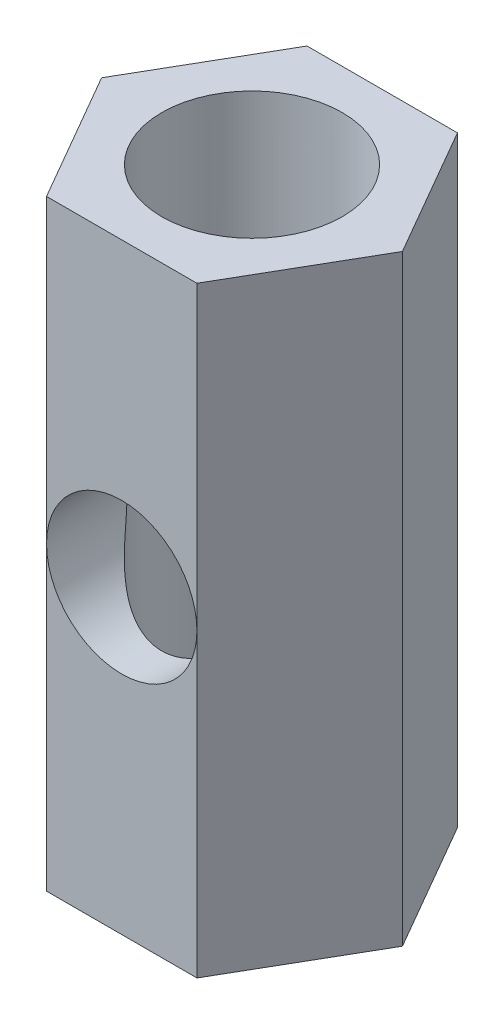
SolidWorks part; units mm, degrees
material "2.0402 (CuZn40Pb2)"
ref_plane "Front" through (0, 0, 0) normal (0, 0, 1) x (1, 0, 0)
ref_plane "Top" through (0, 0, 0) normal (0, 1, 0) x (1, 0, 0)
ref_plane "Right" through (0, 0, 0) normal (1, 0, 0) x (0, 0, -1)
sketch "Эскиз1" plane through (0, 0, 0) normal (0, 1, 0) x (1, 0, 0)
  line L1 (1.25, -2.1651) -> (2.5, 0)
  line L2 (2.5, 0) -> (1.25, 2.1651)
  line L3 (1.25, 2.1651) -> (-1.25, 2.1651)
  line L4 (-1.25, 2.1651) -> (-2.5, 0)
  line L5 (-2.5, 0) -> (-1.25, -2.1651)
  line L6 (-1.25, -2.1651) -> (1.25, -2.1651)
  circle A0 centre (0, 0) radius 2.1651 construction
  circle A1 centre (0, 0) radius 2.5 construction
  dimension "D1" = 5
  dimension "D2" = 2.5
extrude "Бобышка-Вытянуть1" add sketch "Эскиз1" along normal blind 10
sketch "Эскиз2" plane through (0, 10, 0) normal (0, 1, 0) x (1, 0, 0)
  circle A0 centre (0, 0) radius 1.5
  dimension "D1" = 3
extrude "Бобышка-Вытянуть2" add sketch "Эскиз2" along normal blind 5
sketch "Эскиз3" plane through (0, 0, 0) normal (0, -1, 0) x (1, 0, 0)
  circle A0 centre (0, 0) radius 1.5
  dimension "D1" = 3
extrude "Вырез-Вытянуть1" cut sketch "Эскиз3" against normal through all
sketch "Эскиз4" plane through (0, 0, 0) normal (0, 0, 1) x (1, 0, 0)
  line L0 (0, 10) -> (0, 0) construction
  line L1 (-1.25, 10) -> (1.25, 10) construction
  circle A0 centre (0, 5) radius 1.25
  dimension "D1" = 2.5
extrude "Вырез-Вытянуть2" cut sketch "Эскиз4" against normal through all both and the other way through all contours A0
